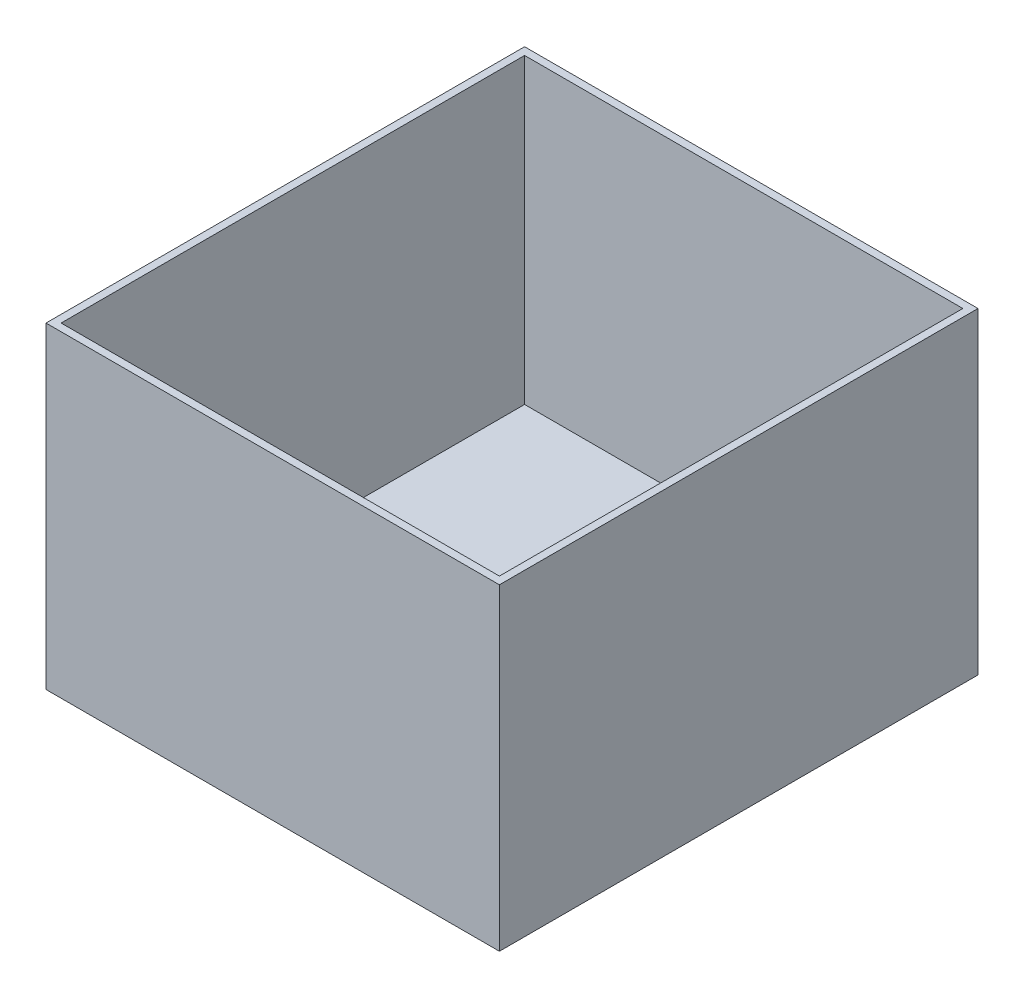
SolidWorks part; units mm, degrees
ref_plane "前视基准面" through (0, 0, 0) normal (0, 0, 1) x (1, 0, 0)
ref_plane "上视基准面" through (0, 0, 0) normal (0, 1, 0) x (1, 0, 0)
ref_plane "右视基准面" through (0, 0, 0) normal (1, 0, 0) x (0, 0, -1)
sketch "草图1" plane through (0, 0, 0) normal (0, 1, 0) x (1, 0, 0)
  line L1 (-45, 47.5) -> (45, 47.5)
  line L2 (-45, 47.5) -> (-45, -47.5)
  line L3 (-45, -47.5) -> (45, -47.5)
  line L4 (45, 47.5) -> (45, -47.5)
  line L5 (-45, 47.5) -> (45, -47.5) construction
  line L6 (-45, -47.5) -> (45, 47.5) construction
  point P0 (0, 0)
  dimension "D1" = 90
  dimension "D2" = 95
extrude "凸台-拉伸1" add sketch "草图1" against normal blind 3
sketch "草图2" plane through (0, 0, 0) normal (0, 1, 0) x (1, 0, 0)
  line L0 (-45, 47.5) -> (-45, -47.5) construction
  line L1 (-43.5, 46) -> (43.5, 46)
  line L2 (-43.5, 46) -> (-43.5, -46)
  line L3 (-43.5, -46) -> (43.5, -46)
  line L4 (43.5, 46) -> (43.5, -46)
  line L5 (45, -47.5) -> (45, 47.5) construction
  line L6 (-45, -47.5) -> (45, -47.5) construction
  line L7 (45, 47.5) -> (-45, 47.5) construction
  line L9 (-45, 47.5) -> (45, 47.5)
  line L10 (-45, 47.5) -> (-45, -47.5)
  line L11 (-45, -47.5) -> (45, -47.5)
  line L12 (45, 47.5) -> (45, -47.5)
  dimension "D1" = 1.5
  dimension "D2" = 1.5
  dimension "D3" = 1.5
  dimension "D4" = 1.5
extrude "凸台-拉伸2" add sketch "草图2" along normal blind 60
sketch "草图3" plane through (0, 0, 0) normal (0, 1, 0) x (1, 0, 0)
  line L0 (43.5, 46) -> (-43.5, 46) construction
  line L1 (-21.5, 46) -> (-20, 46)
  line L2 (-21.5, 46) -> (-21.5, -46)
  line L3 (-21.5, -46) -> (-20, -46)
  line L4 (-20, 46) -> (-20, -46)
  line L5 (-43.5, -46) -> (43.5, -46) construction
  line L6 (-43.5, 46) -> (-43.5, -46) construction
  dimension "D1" = 1.5
  dimension "D2" = 22
